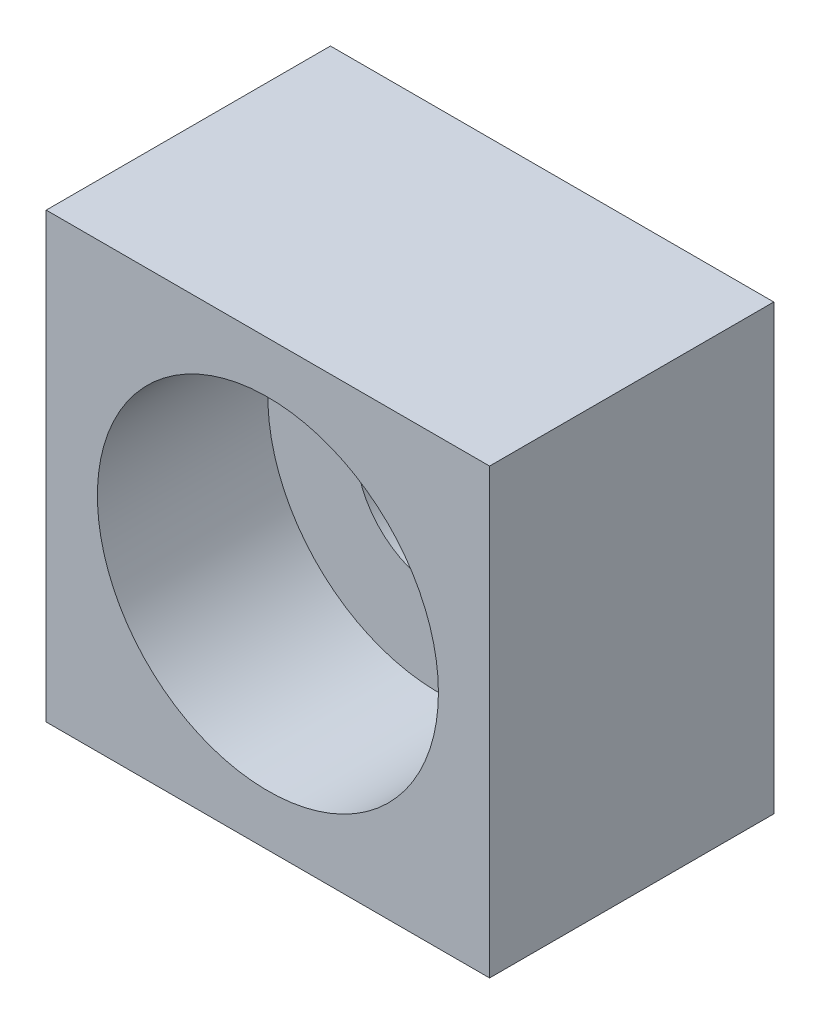
SolidWorks part; units mm, degrees
ref_plane "Спереди" through (0, 0, 0) normal (0, 0, 1) x (1, 0, 0)
ref_plane "Сверху" through (0, 0, 0) normal (0, 1, 0) x (1, 0, 0)
ref_plane "Справа" through (0, 0, 0) normal (1, 0, 0) x (0, 0, -1)
sketch "Эскиз1" plane through (0, 0, 0) normal (0, 0, 1) x (1, 0, 0)
  line L1 (-3.9, -3.9) -> (3.9, -3.9)
  line L2 (-3.9, -3.9) -> (-3.9, 3.9)
  line L3 (-3.9, 3.9) -> (3.9, 3.9)
  line L4 (3.9, -3.9) -> (3.9, 3.9)
  line L5 (-3.9, -3.9) -> (3.9, 3.9) construction
  line L6 (-3.9, 3.9) -> (3.9, -3.9) construction
  circle A0 centre (0, 0) radius 1.45
  point P0 (0, 0)
  dimension "D2" = 2.9
  dimension "D1" = 7.8
extrude "Бобышка-Вытянуть1" add sketch "Эскиз1" along normal blind 5
sketch "Эскиз2" plane through (0, 0, 5) normal (0, 0, 1) x (1, 0, 0)
  circle A0 centre (0, 0) radius 3
  dimension "D1" = 6
extrude "Вырез-Вытянуть1" cut sketch "Эскиз2" against normal blind 3
